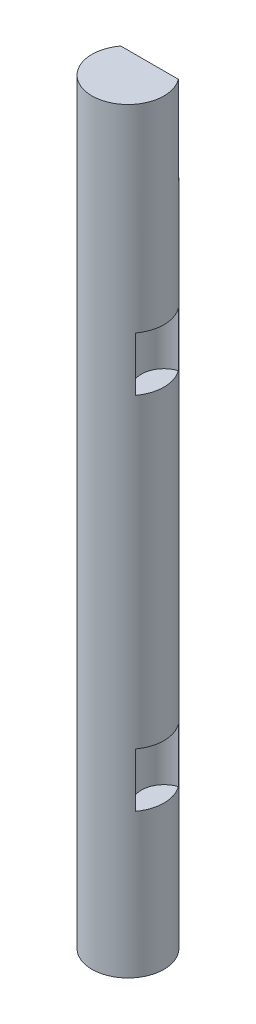
SolidWorks part; units mm, degrees
ref_plane "Alzado" through (0, 0, 0) normal (0, 0, 1) x (1, 0, 0)
ref_plane "Planta" through (0, 0, 0) normal (0, 1, 0) x (1, 0, 0)
ref_plane "Vista lateral" through (0, 0, 0) normal (1, 0, 0) x (0, 0, -1)
sketch "Croquis1" plane through (0, 0, 0) normal (0, 1, 0) x (1, 0, 0)
  circle A0 centre (0, 0) radius 2
  dimension "D1" = 4
extrude "Saliente-Extruir1" add sketch "Croquis1" along normal mid plane 42
sketch "Croquis2" plane through (0, 21, 0) normal (0, 1, 0) x (1, 0, 0)
  line L0 (0, 0) -> (50000, 0) construction
  line L1 (-1.6, 1.2) -> (1.6, 1.2)
  circle A0 centre (0, 0) radius 2 construction
  dimension "D1" = 1.2
extrude "Cortar-Extruir1" cut sketch "Croquis2" against normal blind 5 and the other way through all
sketch "Sketch2" plane through (0, 0, 0) normal (0, 1, 0) x (1, 0, 0)
  line L0 (0, 0) -> (2, 0) construction
  circle A0 centre (2, 0) radius 1.25
  dimension "D1" = 2.5
  dimension "D2" = 2
extrude "Cut-Extrude1" cut sketch "Sketch2" against normal blind 3 from offset 10
pattern_linear "LPattern1" count 2 spacing 20 along (0, -1, 0) of "Cut-Extrude1"
